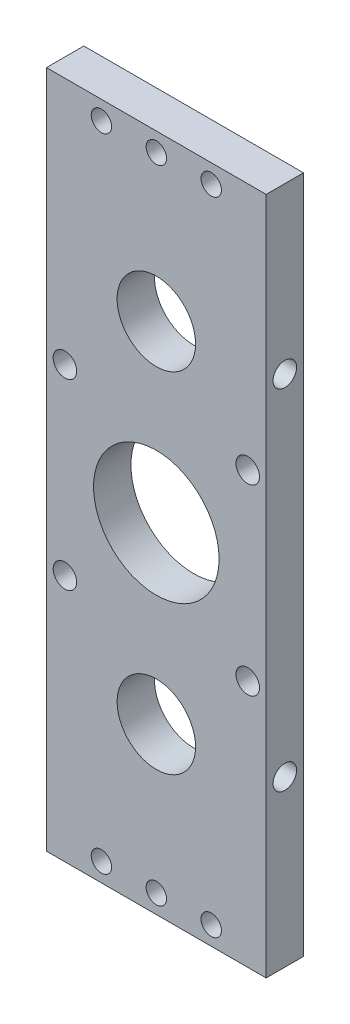
SolidWorks part; units mm, degrees
ref_plane "Plano frontal" through (0, 0, 0) normal (0, 0, 1) x (1, 0, 0)
ref_plane "Plano superior" through (0, 0, 0) normal (0, 1, 0) x (1, 0, 0)
ref_plane "Plano direito" through (0, 0, 0) normal (1, 0, 0) x (0, 0, -1)
sketch "Esboço1" plane through (0, 0, 0) normal (0, 0, 1) x (1, 0, 0)
  line L0 (28, 86.5) -> (-28, -86.5) construction
  line L1 (-28, 86.5) -> (28, 86.5)
  line L2 (-28, 86.5) -> (-28, -86.5)
  line L3 (-28, -86.5) -> (28, -86.5)
  line L4 (28, 86.5) -> (28, -86.5)
  dimension "D1" = 173
  dimension "D2" = 56
extrude "Ressalto-extrusão1" add sketch "Esboço1" along normal blind 9.525
sketch "Esboço2" plane through (0, 0, 9.525) normal (0, 0, 1) x (1, 0, 0)
  line L0 (0, 86.5) -> (0, -86.5) construction
  line L1 (28, 86.5) -> (-28, 86.5) construction
  line L2 (-28, -86.5) -> (28, -86.5) construction
  line L3 (0, 0) -> (-16, 0) construction
  line L4 (-28, 81.74) -> (28, 81.74) construction
  line L5 (-28, 86.5) -> (-28, -86.5) construction
  line L6 (28, -86.5) -> (28, 86.5) construction
  circle A0 centre (0, 0) radius 16
  circle A1 centre (0, 44.47) radius 10
  circle A2 centre (0, -44.47) radius 10
  circle A3 centre (23.3, 23.3) radius 3
  circle A4 centre (23.3, -23.3) radius 3
  circle A5 centre (-23.3, -23.3) radius 3
  circle A6 centre (-23.3, 23.3) radius 3
  circle A7 centre (0, 81.74) radius 2.6
  circle A8 centre (14, 81.74) radius 2.6
  circle A9 centre (-14, 81.74) radius 2.6
  circle A10 centre (14, -81.74) radius 2.6
  circle A11 centre (0, -81.74) radius 2.6
  circle A12 centre (-14, -81.74) radius 2.6
  dimension "D1" = 32
  dimension "D3" = 20
  dimension "D6" = 6
  dimension "D9" = 5.2
  dimension "D10" = 5.2
  dimension "D2" = 44.47
  dimension "D4" = 23.3
  dimension "D5" = 23.3
  dimension "D7" = 4.76
  dimension "D8" = 14
extrude "Corte-extrusão1" cut sketch "Esboço2" against normal up to surface (9.525 mm away) up to face at (0, 0, 0)
sketch "Croquis1" plane through (28, 0, 0) normal (1, 0, 0) x (0, 0, -1)
  line L0 (-4.7625, 86.5) -> (-4.7625, -86.5) construction
  line L1 (-9.525, 86.5) -> (0, 86.5) construction
  line L2 (-9.525, -86.5) -> (0, -86.5) construction
  circle A0 centre (-4.7625, 44.47) radius 2
  circle A1 centre (-4.7625, -44.47) radius 2
  dimension "D1" = 4
  dimension "D2" = 4
  dimension "D3" = 42.03
  dimension "D4" = 42.03
extrude "Cortar-Extruir1" cut sketch "Croquis1" against normal up to next
sketch "Croquis2" plane through (28, 0, 0) normal (1, 0, 0) x (0, 0, -1)
  circle A0 centre (-4.7625, 44.47) radius 3
  circle A1 centre (-4.7625, -44.47) radius 3
  dimension "D1" = 6
  dimension "D2" = 6
extrude "Cortar-Extruir2" cut sketch "Croquis2" against normal blind 7
